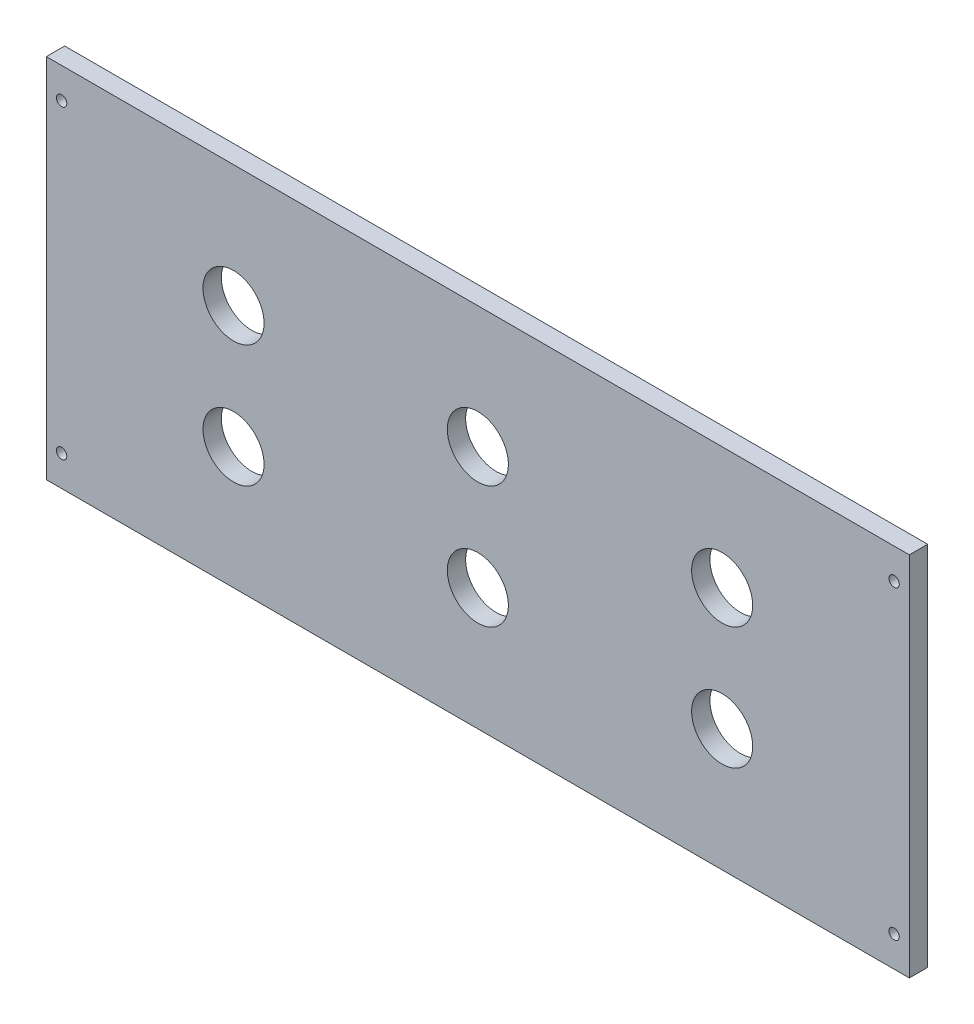
SolidWorks part; units mm, degrees
ref_plane "Front Plane" through (0, 0, 0) normal (0, 0, 1) x (1, 0, 0)
ref_plane "Top Plane" through (0, 0, 0) normal (0, 1, 0) x (1, 0, 0)
ref_plane "Right Plane" through (0, 0, 0) normal (1, 0, 0) x (0, 0, -1)
sketch "Sketch1" plane through (0, 0, 0) normal (0, 0, 1) x (1, 0, 0)
  line L0 (-70.65, 0) -> (70.65, 0) construction
  line L1 (-70.65, -30) -> (70.65, -30)
  line L2 (-70.65, -30) -> (-70.65, 30)
  line L3 (-70.65, 30) -> (70.65, 30)
  line L4 (70.65, -30) -> (70.65, 30)
  line L5 (-70.65, -30) -> (70.65, 30) construction
  line L6 (-70.65, 30) -> (70.65, -30) construction
  line L7 (0, 30) -> (0, -30) construction
  circle A0 centre (-68.15, 25) radius 0.85
  circle A1 centre (-68.15, -25) radius 0.85
  circle A2 centre (68.15, -25) radius 0.85
  circle A3 centre (68.15, 25) radius 0.85
  circle A4 centre (0, -10) radius 5
  circle A5 centre (-40, -10) radius 5
  circle A6 centre (40, -10) radius 5
  circle A7 centre (40, 10) radius 5
  circle A8 centre (0, 10) radius 5
  circle A9 centre (-40, 10) radius 5
  point P0 (0, 0)
  dimension "D3" = 1.7
  dimension "D4" = 5
  dimension "D5" = 2.5
  dimension "D6" = 10
  dimension "D7" = 10
  dimension "D8" = 10
  dimension "D9" = 40
  dimension "D1" = 60
  dimension "D2" = 141.3
extrude "Boss-Extrude1" add sketch "Sketch1" along normal blind 3
